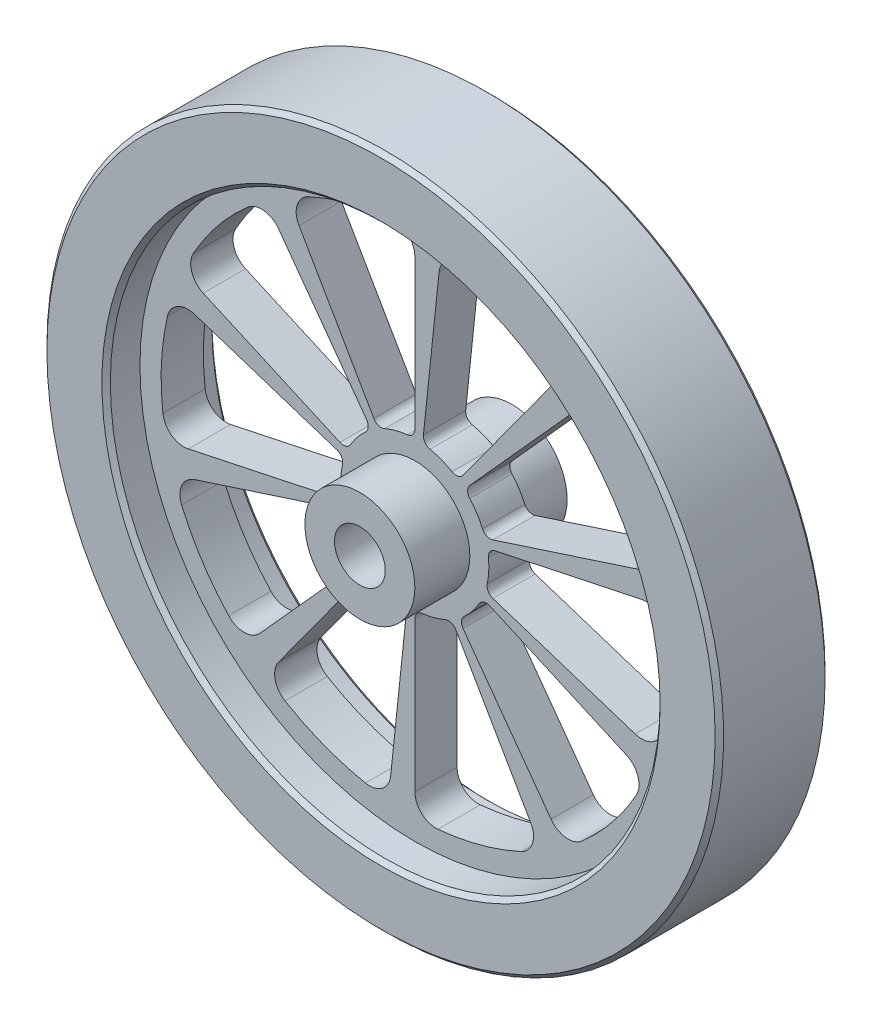
SolidWorks part; units mm, degrees
ref_plane "Front Plane" through (0, 0, 0) normal (0, 0, 1) x (1, 0, 0)
ref_plane "Top Plane" through (0, 0, 0) normal (0, 1, 0) x (1, 0, 0)
ref_plane "Right Plane" through (0, 0, 0) normal (1, 0, 0) x (0, 0, -1)
sketch "Sketch3" plane through (0, 0, 0) normal (0, 0, 1) x (1, 0, 0)
  circle A0 centre (0, 0) radius 80
  circle A1 centre (0, 0) radius 6
  dimension "D1" = 12
  dimension "D2" = 160
extrude "Boss-Extrude2" add sketch "Sketch3" along normal mid plane 26
sketch "Sketch4" plane through (0, 0, 13) normal (0, 0, 1) x (1, 0, 0)
  circle A0 centre (0, 0) radius 65
  dimension "D1" = 130
extrude "Cut-Extrude3" cut sketch "Sketch4" against normal blind 8
mirror "Mirror2" about plane through (0, 0, 0) normal (0, 0, 1) of "Cut-Extrude3"
sketch "Sketch5" plane through (0, 0, 0) normal (0, 0, 1) x (1, 0, 0)
  circle A0 centre (0, 0) radius 6 construction
  circle A1 centre (0, 0) radius 6
  circle A2 centre (0, 0) radius 13
  dimension "D1" = 26
extrude "Boss-Extrude3" add sketch "Sketch5" along normal mid plane 36
chamfer "Chamfer1" distance 1 angle 45 2 edges at (80, 0, -13) (80, 0, 13)
sketch "Sketch6" plane through (0, 0, 5) normal (0, 0, 1) x (1, 0, 0)
  line L0 (0, 17.5) -> (0, 60) construction
  line L1 (0, 0) -> (-30, 51.9615) construction
  line L2 (-27.3861, 47.4342) -> (-9.6986, 16.7984)
  line L3 (0, 54.7723) -> (0, 19.3972)
  arc A0 (-5.4545, 59.7516) -> (-25.152, 54.4736) centre (0, 0) ccw
  arc A1 (-1.7949, 17.4077) -> (-7.1495, 15.973) centre (0, 0) ccw
  arc A2 (-27.3861, 47.4342) -> (-25.152, 54.4736) centre (-23.056, 49.9342) cw
  arc A3 (0, 54.7723) -> (-5.4545, 59.7516) centre (-5, 54.7723) ccw
  arc A4 (-7.1495, 15.973) -> (-9.6986, 16.7984) centre (-7.9665, 17.7984) cw
  arc A5 (0, 19.3972) -> (-1.7949, 17.4077) centre (-2, 19.3972) cw
  point P14 (-8.75, 15.1554)
  dimension "D1" = 35
  dimension "D2" = 120
  dimension "D4" = 5
  dimension "D5" = 2
  dimension "D3" = 30
extrude "Cut-Extrude4" cut sketch "Sketch6" against normal through all
pattern_circular "CirPattern1" count 10 over 360 about axis through (0, 0, 0) along (0, 0, 1) of "Cut-Extrude4"
